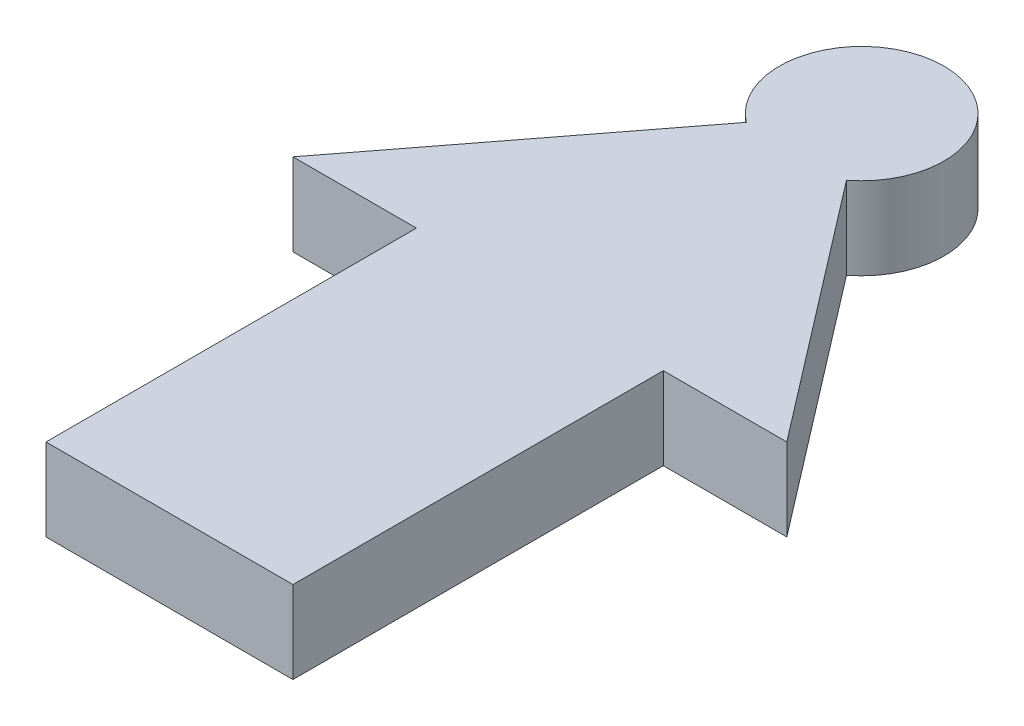
SolidWorks part; units mm, degrees
ref_plane "Front Plane" through (0, 0, 0) normal (0, 0, 1) x (1, 0, 0)
ref_plane "Top Plane" through (0, 0, 0) normal (0, 1, 0) x (1, 0, 0)
ref_plane "Right Plane" through (0, 0, 0) normal (1, 0, 0) x (0, 0, -1)
sketch "Sketch1" plane through (0, 0, 0) normal (0, 1, 0) x (1, 0, 0)
  line L0 (-76.2, 57.15) -> (76.2, 57.15)
  line L1 (-38.1, 57.15) -> (38.1, 57.15)
  line L2 (-38.1, 57.15) -> (-38.1, -57.15)
  line L3 (-38.1, -57.15) -> (38.1, -57.15)
  line L4 (38.1, 57.15) -> (38.1, -57.15)
  line L5 (-38.1, 57.15) -> (38.1, -57.15) construction
  line L6 (-38.1, -57.15) -> (38.1, 57.15) construction
  line L7 (0, 0) -> (0, 216.8912) construction
  line L8 (-76.2, 57.15) -> (0, 156.4558)
  line L9 (76.2, 57.15) -> (0, 156.4558)
  circle A0 centre (0, 156.4558) radius 25.4
  point P0 (0, 0)
  point P6 (0, 57.15)
  point P9 (0, 57.15)
  dimension "D5" = 50.8
  dimension "D1" = 76.2
  dimension "D2" = 114.3
  dimension "D3" = 152.4
  dimension "D4" = 52.5
extrude "Boss-Extrude1" add sketch "Sketch1" along normal blind 25.4 contours L0 L9 L8 | L4 L0 L2 L3 | L9 A0 L8 | L8 A0 L9
